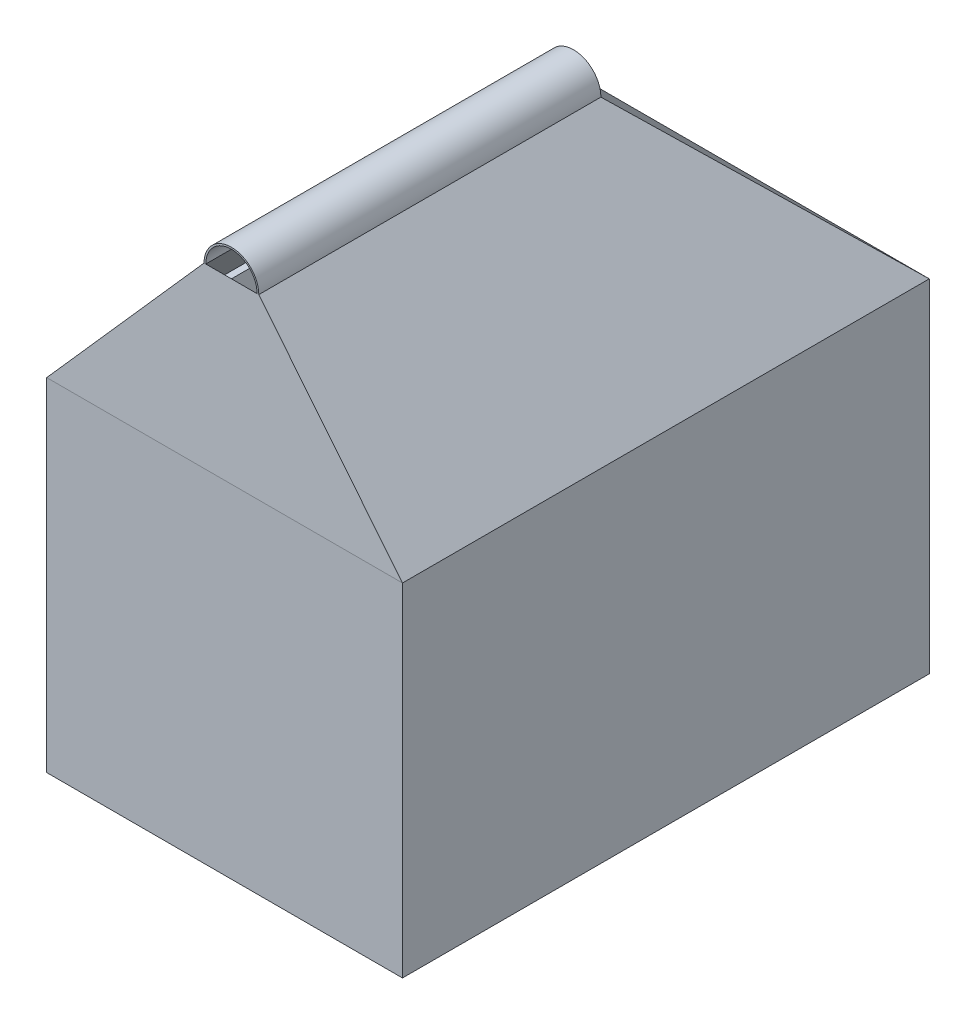
SolidWorks part; units mm, degrees
ref_plane "Front Plane" through (0, 0, 0) normal (0, 0, 1) x (1, 0, 0)
ref_plane "Top Plane" through (0, 0, 0) normal (0, 1, 0) x (1, 0, 0)
ref_plane "Right Plane" through (0, 0, 0) normal (1, 0, 0) x (0, 0, -1)
sketch "Sketch1" plane through (0, 0, 0) normal (0, 1, 0) x (1, 0, 0)
  line L0 (-4, -4) -> (204, -4)
  line L1 (0, 0) -> (200, 0)
  line L2 (0, 0) -> (0, 300)
  line L3 (0, 300) -> (200, 300)
  line L4 (200, 0) -> (200, 300)
  line L5 (204, -4) -> (204, 304)
  line L6 (-4, 304) -> (204, 304)
  line L7 (-4, -4) -> (-4, 304)
  dimension "D1" = 200
  dimension "D2" = 300
  dimension "D3" = 4
extrude "Boss-Extrude1" add sketch "Sketch1" along normal blind 200
sketch "Sketch2" plane through (0, 200, 0) normal (0, 1, 0) x (1, 0, 0)
  line L1 (-4, 304) -> (204, 304)
  line L2 (-4, 304) -> (-4, -4)
  line L3 (-4, -4) -> (204, -4)
  line L4 (204, 304) -> (204, -4)
ref_plane "Plane1" through (0, 300, 0) normal (0, 1, 0) x (1, 0, 0)
sketch "Sketch3" plane through (0, 300, 0) normal (0, 1, 0) x (1, 0, 0)
  line L1 (84, 200) -> (116, 200)
  line L2 (84, 200) -> (84, 0)
  line L3 (84, 0) -> (116, 0)
  line L4 (116, 200) -> (116, 0)
  line L6 (0, 300) -> (0, 0) construction
  line L7 (200, 300) -> (0, 300) construction
  dimension "D1" = 200
  dimension "D2" = 32
  dimension "D3" = 84
  dimension "D4" = 100
surface "Surface-Loft1"
sketch "Sketch4" plane through (0, 0, -304) normal (0, 0, -1) x (-1, 0, 0)
  line L1 (-84, 300) -> (-116, 300) construction
  line L2 (4, 200) -> (-84, 300) construction
  line L3 (-116, 300) -> (-115, 300)
  line L4 (-85, 300) -> (-84, 300)
  arc A0 (-84, 300) -> (-116, 300) centre (-100, 300) ccw
  arc A1 (-85, 300) -> (-115, 300) centre (-100, 300) ccw
  dimension "D1" = 1
extrude "Boss-Extrude2" add sketch "Sketch4" along normal blind 200 from offset 304 separate body
